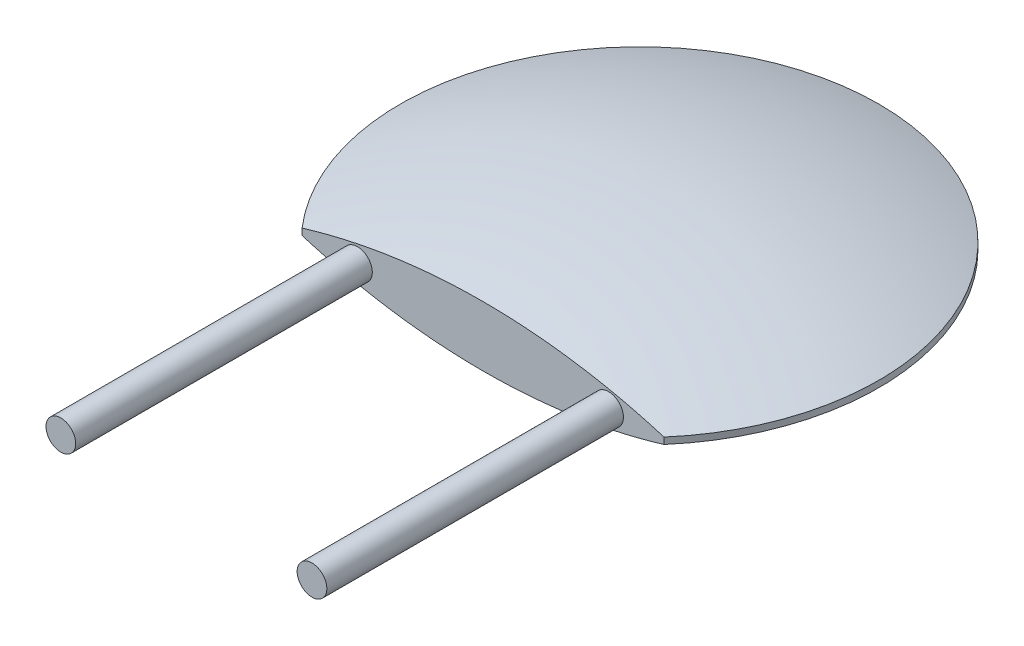
SolidWorks part; units mm, degrees
ref_plane "前视基准面" through (0, 0, 0) normal (0, 0, 1) x (1, 0, 0)
ref_plane "上视基准面" through (0, 0, 0) normal (0, 1, 0) x (1, 0, 0)
ref_plane "右视基准面" through (0, 0, 0) normal (1, 0, 0) x (0, 0, -1)
sketch "草图1" plane through (0, 0, 0) normal (1, 0, 0) x (0, 0, -1)
  line L0 (0, -1000) -> (0, 49000) construction
  line L1 (-1000, 0) -> (49000, 0) construction
  line L2 (-2.5, 0.5) -> (2.5, 0.5) construction
  line L3 (2.5, 0.5) -> (2.5, -0.5) construction
  line L4 (-2.5, 0.5) -> (-2.5, -0.5) construction
  line L5 (-2.5, -0.5) -> (2.5, -0.5) construction
  line L6 (0, 0.5) -> (0, -0.5)
  line L7 (2.4201, 0.1392) -> (2.4201, -0.2216) construction
  line L8 (2.4201, 0.0327) -> (2.4201, -0.0327)
  arc A0 (0, 0.5) -> (2.4201, 0.0327) centre (0, -6) cw
  arc A1 (0, -0.5) -> (2.4201, -0.0327) centre (0, 6) ccw
  point P10 (0, 0.5)
  point P11 (2.5, 0)
  point P12 (-2.5, 0)
  dimension "D1" = 0.5
  dimension "D2" = 2.5
revolve "旋转1" add sketch "草图1" angle 360 about L0
sketch "草图3" plane through (0, 0, 0) normal (0, 1, 0) x (1, 0, 0)
  line L0 (-2.8155, -1.5834) -> (2.9791, -1.5834)
  line L1 (2.9791, -1.5834) -> (2.9791, -2.5171)
  line L2 (2.9791, -2.5171) -> (-2.8155, -2.5171)
  line L3 (-2.8155, -2.5171) -> (-2.8155, -1.5834)
extrude "切除-拉伸1" cut sketch "草图3" against normal mid plane 10
ref_plane "基准面1" through (0, 0, 1.5834) normal (0, 0, 1) x (1, 0, 0)
sketch "草图4" plane through (0, 0, 1.5834) normal (0, 0, 1) x (1, 0, 0)
  line L0 (0, -1000) -> (0, 49000) construction
  line L1 (-1000, 0) -> (49000, 0) construction
  line L2 (-1.27, 0.4909) -> (-1.27, -0.7298) construction
  line L3 (1.27, 0.4909) -> (1.27, -0.7298) construction
  circle A0 centre (-1.27, 0) radius 0.15
  circle A1 centre (1.27, 0) radius 0.15
  dimension "D2" = 0.3
  dimension "D1" = 2.54
extrude "凸台-拉伸1" add sketch "草图4" along normal blind 3
